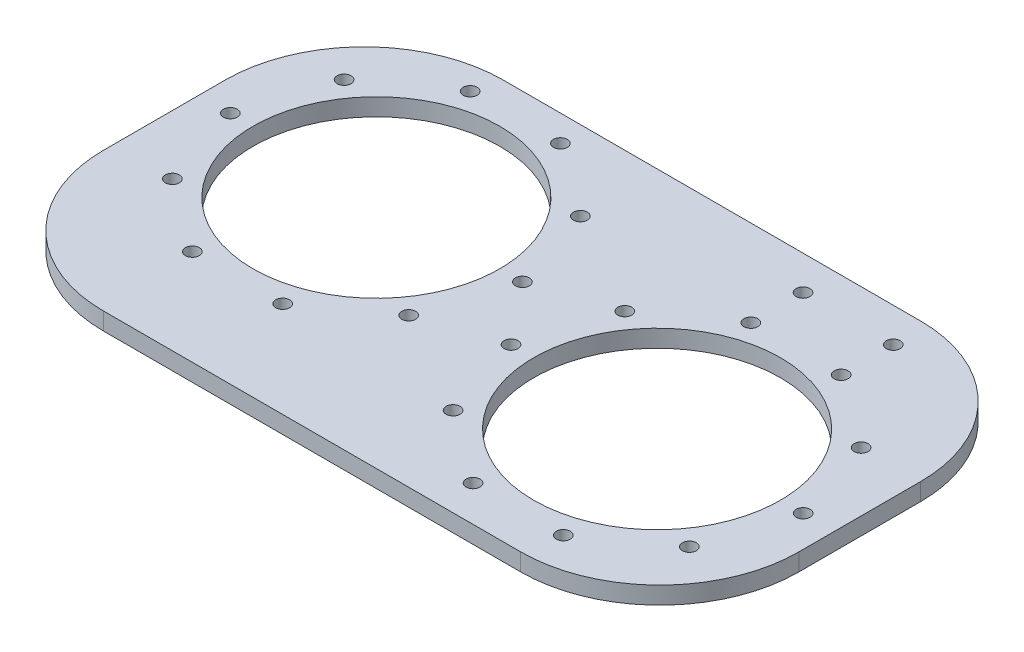
SolidWorks part; units mm, degrees
ref_plane "前基準面" through (0, 0, 0) normal (0, 0, 1) x (1, 0, 0)
ref_plane "上基準面" through (0, 0, 0) normal (0, 1, 0) x (1, 0, 0)
ref_plane "右基準面" through (0, 0, 0) normal (1, 0, 0) x (0, 0, -1)
sketch "草圖1" plane through (0, 0, 0) normal (0, 1, 0) x (1, 0, 0)
  line L0 (49, -7.28) -> (-49, 10) construction
  line L1 (-60, 57.5) -> (60, 57.5)
  line L2 (-100, 17.5) -> (-100, -17.5)
  line L3 (-60, -57.5) -> (60, -57.5)
  line L4 (100, 17.5) -> (100, -17.5)
  line L5 (-100, 57.5) -> (100, -57.5) construction
  line L6 (-100, -57.5) -> (100, 57.5) construction
  line L7 (-49, 10) -> (49, 10) construction
  arc A0 (-100, 17.5) -> (-60, 57.5) centre (-60, 17.5) cw
  arc A1 (60, -57.5) -> (100, -17.5) centre (60, -17.5) ccw
  arc A2 (-60, -57.5) -> (-100, -17.5) centre (-60, -17.5) cw
  arc A3 (100, 17.5) -> (60, 57.5) centre (60, 17.5) ccw
  circle A4 centre (-49, 10) radius 35.5
  circle A5 centre (49, -7.28) radius 35.5
  point P0 (0, 0)
  point P24 (0, 57.5)
  point P25 (0, 10)
  dimension "D2" = 40
  dimension "D5" = 71
  dimension "D6" = 10
  dimension "D3" = 200
  dimension "D4" = 115
  dimension "D7" = 10
  dimension "D8" = 98
extrude "填料-伸長1" add sketch "草圖1" along normal blind 5
sketch "草圖2" plane through (0, 5, 0) normal (0, 1, 0) x (1, 0, 0)
  circle A0 centre (49, -7.28) radius 42 construction
  circle A1 centre (91, -7.28) radius 2
  dimension "D1" = 84
  dimension "D2" = 4
extrude "除料-伸長1" cut sketch "草圖2" against normal up to next
pattern_circular "環狀複製排列1" count 10 over 360 about axis through (49, 0, 7.28) along (0, 1, 0) of "除料-伸長1"
sketch "草圖3" plane through (0, 5, 0) normal (0, 1, 0) x (1, 0, 0)
  circle A0 centre (-49, 10) radius 42 construction
  circle A1 centre (-7, 10) radius 2
  circle A2 centre (15.0213, 17.4069) radius 2 construction
  dimension "D1" = 84
extrude "除料-伸長2" cut sketch "草圖3" against normal up to next
pattern_circular "環狀複製排列2" count 10 over 360 about axis through (-49, 0, -10) along (0, 1, 0) of "除料-伸長2"
sketch "草圖4" plane through (0, 5, 0) normal (0, 1, 0) x (1, 0, 0)
  circle A0 centre (36.0213, 47.6643) radius 2
  circle A1 centre (61.9787, 47.6643) radius 2
  circle A2 centre (61.9787, 32.6643) radius 2 construction
  point P4 (36.0213, 32.6643)
  point P5 (61.9787, 32.6643)
  dimension "D1" = 15
extrude "除料-伸長3" cut sketch "草圖4" against normal up to next
